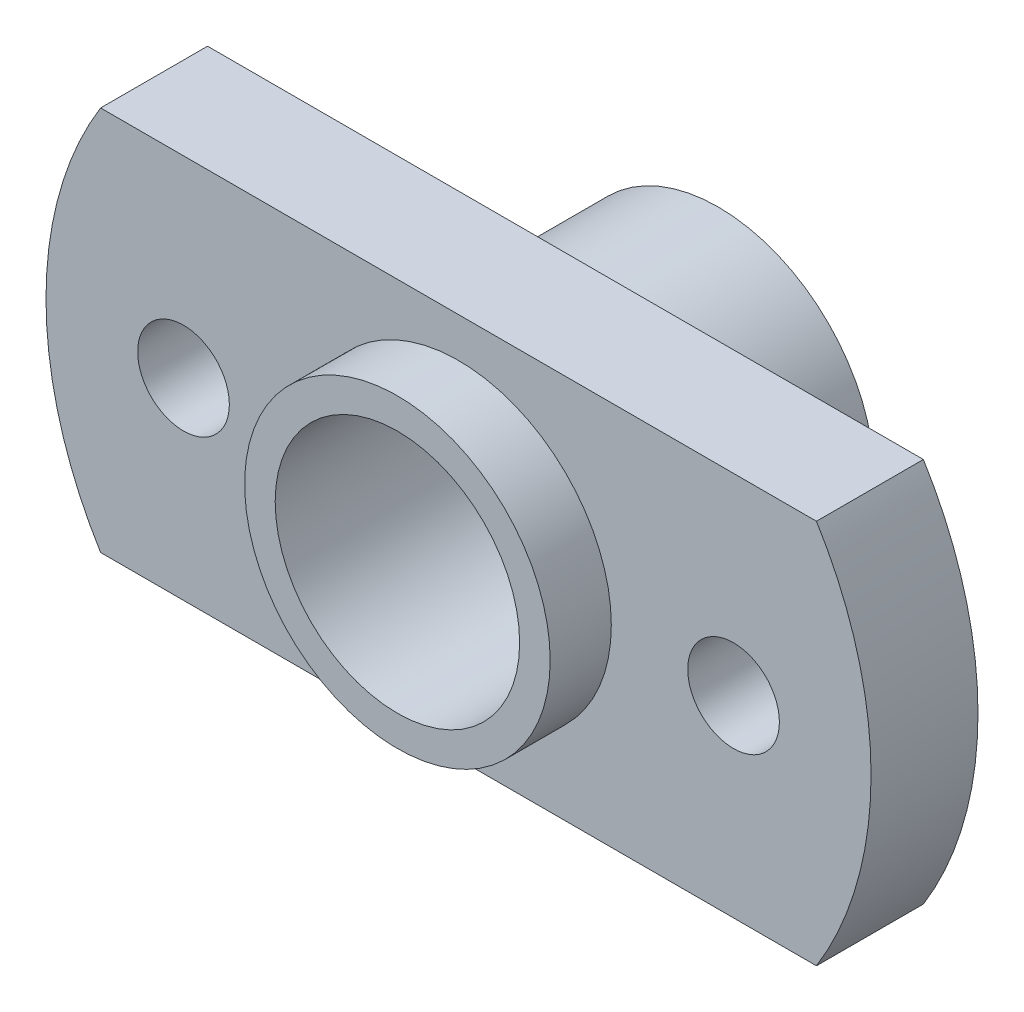
SolidWorks part; units mm, degrees
material "Latón"
ref_plane "Alzado" through (0, 0, 0) normal (0, 0, 1) x (1, 0, 0)
ref_plane "Planta" through (0, 0, 0) normal (0, 1, 0) x (1, 0, 0)
ref_plane "Vista lateral" through (0, 0, 0) normal (1, 0, 0) x (0, 0, -1)
ref_plane "Plano1" through (0, 0, 177.0264) normal (0, 0, -1) x (-1, 0, 0)
sketch "Croquis1" plane through (0, 0, 177.0264) normal (0, 0, -1) x (-1, 0, 0)
  line L0 (177.8132, -74.2001) -> (154.3868, -74.2001)
  line L1 (154.3868, -86.8001) -> (177.8132, -86.8001)
  arc A0 (154.3868, -74.2001) -> (154.3868, -86.8001) centre (164.6, -80.5001) ccw
  arc A1 (177.8132, -86.8001) -> (177.8132, -74.2001) centre (167.6, -80.5001) ccw
extrude "Saliente-Extruir1" add sketch "Croquis1" against normal blind 3.5
ref_plane "Plano2" through (0, -80.5001, 0) normal (0, 1, 0) x (1, 0, 0)
sketch "Croquis2" plane through (0, -80.5001, 0) normal (0, 1, 0) x (1, 0, 0)
  line L0 (-161.1, -180.5264) -> (-166.1, -180.5264)
  line L1 (-166.1, -180.5264) -> (-166.1, -182.5264)
  line L2 (-166.1, -182.5264) -> (-161.1, -182.5264)
  line L3 (-161.1, -182.5264) -> (-161.1, -180.5264)
  line L4 (-166.1, -180.5264) -> (-166.1, -182.5264) construction
revolve "Revolución1" add sketch "Croquis2" angle 360 about L4
ref_plane "Plano3" through (0, -80.5001, 0) normal (0, -1, 0) x (1, 0, 0)
sketch "Croquis3" plane through (0, -80.5001, 0) normal (0, -1, 0) x (1, 0, 0)
  line L0 (-161, 177.0264) -> (-166.1, 177.0264)
  line L1 (-166.1, 177.0264) -> (-166.1, 172.0264)
  line L2 (-166.1, 172.0264) -> (-161, 172.0264)
  line L3 (-161, 172.0264) -> (-161, 177.0264)
  line L4 (-166.1, 177.0264) -> (-166.1, 172.0264) construction
revolve "Revolución2" add sketch "Croquis3" angle 360 about L4
hole_wizard "Diámetro de taladro Ø3.0 (3)1" positions "Croquis5" profile "Croquis4" hole size "Ø3.0" standard "Ansi Metric"
sketch "Croquis5" plane through (0, 0, 180.5264) normal (0, 0, 1) x (1, 0, 0)
  point P0 (-157.1, -80.5001)
  point P1 (-175.1, -80.5001)
sketch "Croquis4" plane through (-157.1, -80.5001, 180.5264) normal (1, 0, 0) x (0, -1, 0)
  line L0 (0, 0) -> (0, 8.5)
  line L1 (0, 8.5) -> (1.5, 8.5)
  line L2 (1.5, 8.5) -> (1.5, 0)
  line L5 (1.5, 0) -> (0, 0)
  line L11 (0, -6.35) -> (0, 107.95) construction
  dimension "Diámetro de taladro hasta el siguiente" = 3
  dimension "Profundidad de taladro hasta el siguiente" = 8.5
hole_wizard "Diámetro de taladro Ø8.0 (8)1" positions "Croquis7" profile "Croquis6" hole size "Ø8.0" standard "Ansi Metric"
sketch "Croquis7" plane through (0, 0, 172.0264) normal (0, 0, -1) x (-1, 0, 0)
  point P0 (166.1, -80.5001)
sketch "Croquis6" plane through (-166.1, -80.5001, 172.0264) normal (1, 0, 0) x (0, 1, 0)
  line L0 (0, 0) -> (0, 10.5)
  line L1 (0, 10.5) -> (4, 10.5)
  line L2 (4, 10.5) -> (4, 0)
  line L5 (4, 0) -> (0, 0)
  line L11 (0, -6.35) -> (0, 107.95) construction
  dimension "Diámetro de taladro hasta el siguiente" = 8
  dimension "Profundidad de taladro hasta el siguiente" = 10.5
